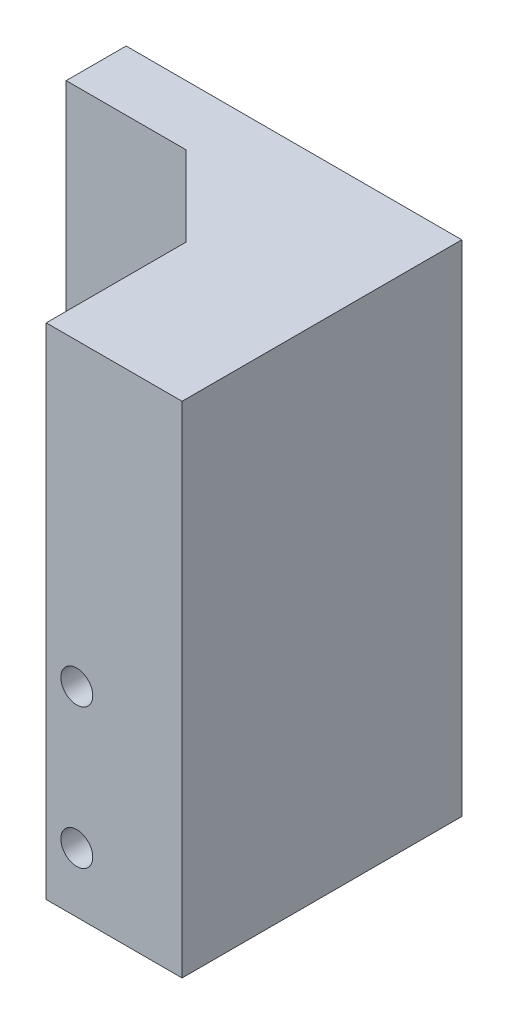
SolidWorks part; units mm, degrees
ref_plane "Alzado" through (0, 0, 0) normal (0, 0, 1) x (1, 0, 0)
ref_plane "Planta" through (0, 0, 0) normal (0, 1, 0) x (1, 0, 0)
ref_plane "Vista lateral" through (0, 0, 0) normal (1, 0, 0) x (0, 0, -1)
sketch "Croquis1" plane through (0, 0, 0) normal (0, 0, 1) x (1, 0, 0)
  line L0 (5, -10) -> (0, -10) construction
  line L1 (0, 0) -> (16.8, 0)
  line L2 (0, 0) -> (0, -20)
  line L3 (0, -20) -> (16.8, -20)
  line L4 (16.8, 0) -> (16.8, -20)
  circle A0 centre (5, -10) radius 2.5
  dimension "D1" = 5
  dimension "D2" = 20
  dimension "D3" = 16.8
  dimension "D4" = 5
extrude "Saliente-Extruir1" add sketch "Croquis1" along normal blind 3
sketch "Croquis2" plane through (0, 0, 3) normal (0, 0, 1) x (1, 0, 0)
  line L0 (16.8, 0) -> (0, 0) construction
  line L1 (10, 0) -> (16.8, 0)
  line L2 (10, 0) -> (10, -20)
  line L3 (10, -20) -> (16.8, -20)
  line L4 (16.8, 0) -> (16.8, -20)
  dimension "D1" = 6.8
extrude "Saliente-Extruir2" add sketch "Croquis2" along normal blind 11
sketch "Croquis3" plane through (0, -20, 0) normal (0, -1, 0) x (1, 0, 0)
  line L6 (0, 0) -> (16.8, 0)
  line L7 (16.8, 0) -> (16.8, 14)
  line L8 (16.8, 14) -> (10, 14)
  line L9 (10, 14) -> (10, 3)
  line L10 (10, 3) -> (0, 3)
  line L11 (0, 3) -> (0, 0)
  line L12 (0, 0) -> (16.8, 0)
  line L13 (16.8, 0) -> (16.8, 14)
  line L14 (16.8, 14) -> (10, 14)
  line L15 (10, 14) -> (10, 3)
  line L16 (10, 3) -> (0, 3)
  line L17 (0, 3) -> (0, 0)
  dimension "D1" = 0
extrude "Saliente-Extruir3" add sketch "Croquis3" along normal blind 5
sketch "Croquis4" plane through (0, 0, 0) normal (0, 1, 0) x (1, 0, 0)
  line L0 (6, -3) -> (10, -3)
  line L1 (10, -3) -> (0, -3) construction
  line L2 (10, -3) -> (10, -7)
  line L3 (10, -14) -> (10, -3) construction
  line L4 (10, -7) -> (6, -3)
  dimension "D1" = 4
extrude "Saliente-Extruir4" add sketch "Croquis4" against normal blind 2
sketch "Croquis5" plane through (0, 0, 14) normal (0, 0, 1) x (1, 0, 0)
  circle A0 centre (11.5298, -22) radius 1.1
  circle A1 centre (11.5298, -15) radius 1.1
hole_wizard "Taladro roscado M21" positions "Croquis6" profile "Croquis7" tap size "M2" standard "ISO"
sketch "Croquis6" plane through (0, 0, 14) normal (0, 0, 1) x (1, 0, 0)
  point P0 (11.5298, -15)
  point P3 (11.5298, -22)
sketch "Croquis7" plane through (11.5298, -15, 14) normal (1, 0, 0) x (0, -1, 0)
  line L0 (0, 0) -> (0, 10.4807)
  line L1 (0, 10.4807) -> (0.8, 10)
  line L2 (0.8, 10) -> (0.8, 0)
  line L5 (0.8, 0) -> (0, 0)
  line L10 (0, 10.4807) -> (-0.8, 10) construction
  line L11 (0, -6.35) -> (0, 107.95) construction
  dimension "Diámetro de perforador para roscar" = 1.6
  dimension "Profundidad de perforador para roscar" = 10
  dimension "Ángulo de perforador" = 118
sketch "Croquis8" plane through (0, 0, 3) normal (0, 0, 1) x (1, 0, 0)
  line L0 (10, -2) -> (10, -25) construction
  line L1 (0, -25) -> (10, -25)
  line L2 (0, -25) -> (0, -20)
  line L3 (0, -20) -> (10, -20)
  line L4 (10, -25) -> (10, -20)
  line L5 (6, 0) -> (0, 0) construction
  dimension "D1" = 20
extrude "Cortar-Extruir1" cut sketch "Croquis8" against normal blind 10
ref_plane "Plano1" through (0, -10, 0) normal (0, 1, 0) x (1, 0, 0)
mirror "Simetría1" about plane through (0, -10, 0) normal (0, 1, 0) of "Saliente-Extruir4"
